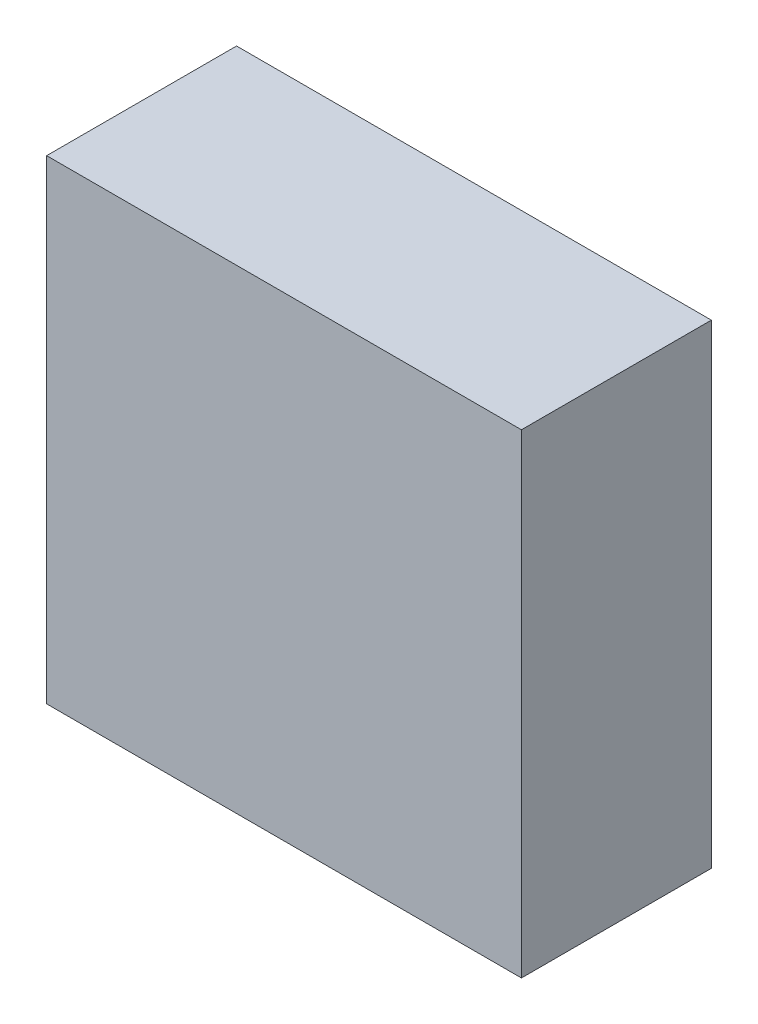
SolidWorks part; units mm, degrees
material "Custom Plastic"
ref_plane "X-Y Datum" through (0, 0, 0) normal (0, 0, 1) x (1, 0, 0)
ref_plane "X-Z Datum" through (0, 0, 0) normal (0, 1, 0) x (1, 0, 0)
ref_plane "Y-Z Datum" through (0, 0, 0) normal (1, 0, 0) x (0, 0, -1)
sketch "Sketch1" plane through (0, 0, 0) normal (0, 0, 1) x (1, 0, 0)
  line L1 (0, 0) -> (50, 0)
  line L2 (0, 0) -> (0, 50)
  line L3 (0, 50) -> (50, 50)
  line L4 (50, 0) -> (50, 50)
extrude "Boss-Extrude1" add sketch "Sketch1" along normal blind 20
